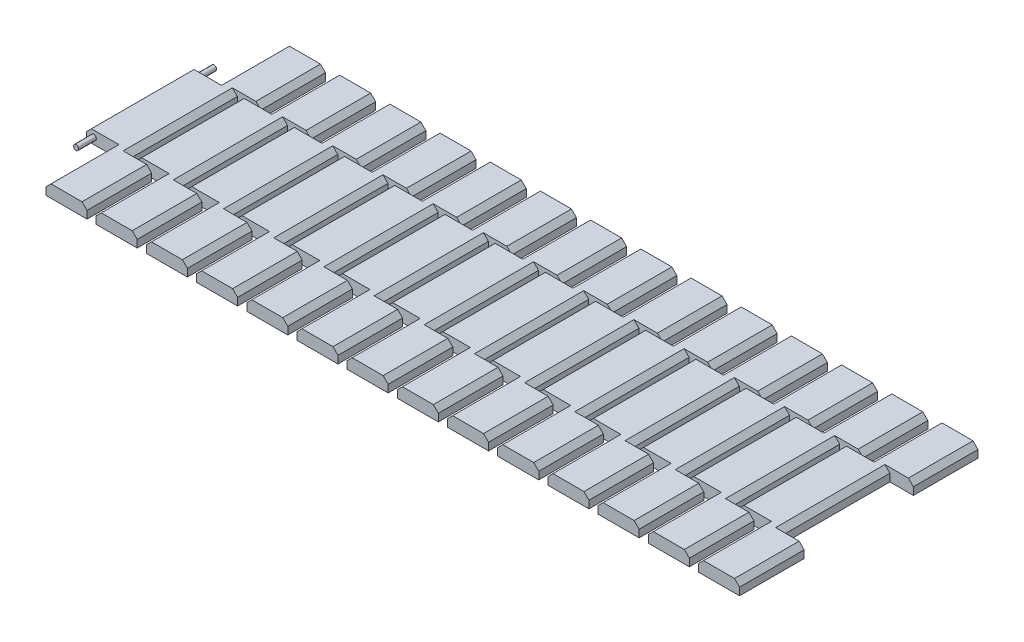
SolidWorks part; units mm, degrees
ref_plane "Front Plane" through (0, 0, 0) normal (0, 0, 1) x (1, 0, 0)
ref_plane "Top Plane" through (0, 0, 0) normal (0, 1, 0) x (1, 0, 0)
ref_plane "Right Plane" through (0, 0, 0) normal (1, 0, 0) x (0, 0, -1)
sketch "Sketch1" plane through (0, 0, 0) normal (0, 1, 0) x (1, 0, 0)
  line L0 (8.1733, -21.7652) -> (8.1733, -47.5096)
  line L1 (-8.1733, 47.5096) -> (8.1733, 47.5096)
  line L2 (-8.1733, 47.5096) -> (-8.1733, 20.437)
  line L3 (-8.1733, -47.5096) -> (8.1733, -47.5096)
  line L4 (8.1733, 47.5096) -> (8.1733, 21.7652)
  line L5 (-8.1733, -20.437) -> (-8.1733, -47.5096)
  line L7 (-19.1472, 20.437) -> (-8.1733, 20.437)
  line L8 (-19.1472, 20.437) -> (-19.1472, -20.437)
  line L9 (-19.1472, -20.437) -> (-8.1733, -20.437)
  line L13 (8.1733, -21.7652) -> (-1.1853, -21.7652)
  line L15 (8.1733, 21.7652) -> (-1.1853, 21.7652)
  line L16 (-1.1853, -21.7652) -> (-1.1853, 21.7652)
  point P0 (0, 0)
  point P6 (-11.9202, -1.9841)
  point P12 (8.1733, 0)
  dimension "D1" = 95.0193
extrude "Boss-Extrude1" add sketch "Sketch1" along normal blind 5
chamfer "Chamfer1" distance 2 angle 45 6 edges at (8.1733, 5, -34.6374) (-8.1733, 5, -33.9733) (-1.1853, 5, 0) (8.1733, 5, 34.6374) (-8.1733, 5, 33.9733) (-19.1472, 5, 0)
sketch "Sketch3" plane through (0, 0, 20.437) normal (0, 0, 1) x (1, 0, 0)
  circle A0 centre (-16.2147, 2.5) radius 1.0217
ref_plane "Plane1" through (0, 0, 0) normal (0, 0, -1) x (-1, 0, 0)
extrude "Boss-Extrude2" add sketch "Sketch3" along normal mid plane 55 from surface at -20.437 contours A0 starting at plane "Plane1"
pattern_linear "LPattern5" count 14 spacing 20 along (-1, 0, 0) of bodies 115 101
